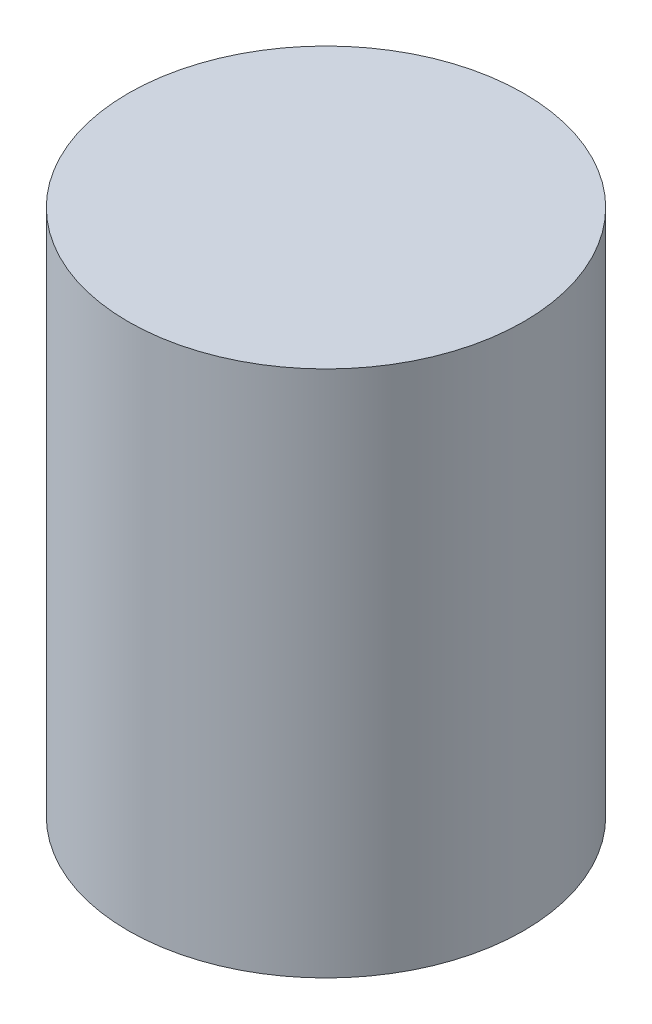
SolidWorks part; units mm, degrees
ref_plane "Front Plane" through (0, 0, 0) normal (0, 0, 1) x (1, 0, 0)
ref_plane "Top Plane" through (0, 0, 0) normal (0, 1, 0) x (1, 0, 0)
ref_plane "Right Plane" through (0, 0, 0) normal (1, 0, 0) x (0, 0, -1)
sketch "Sketch1" plane through (0, 0, 0) normal (0, 1, 0) x (1, 0, 0)
  circle A0 centre (0, 0) radius 90
  dimension "D1" = 180
extrude "Boss-Extrude1" add sketch "Sketch1" along normal blind 240
shell "Shell1" thickness 12
